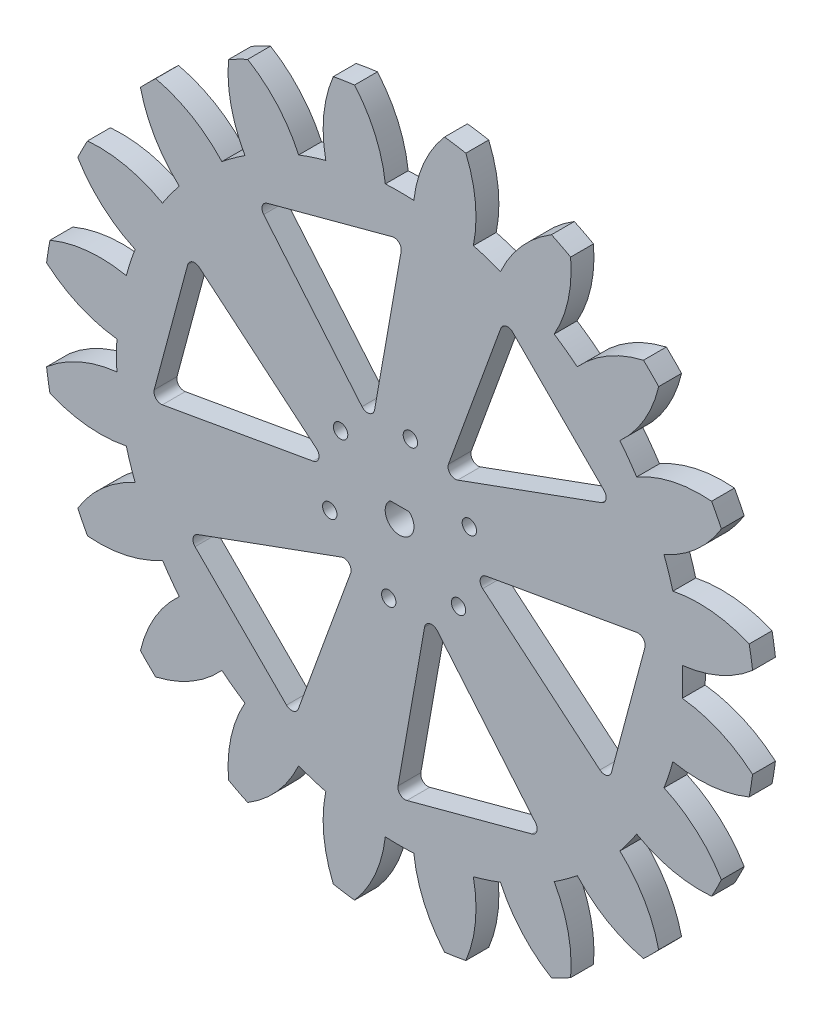
SolidWorks part; units mm, degrees
ref_plane "Front Plane" through (0, 0, 0) normal (0, 0, 1) x (1, 0, 0)
ref_plane "Top Plane" through (0, 0, 0) normal (0, 1, 0) x (1, 0, 0)
ref_plane "Right Plane" through (0, 0, 0) normal (1, 0, 0) x (0, 0, -1)
sketch "Sketch1" plane through (0, 0, 0) normal (0, 0, 1) x (1, 0, 0)
  circle A1 centre (0, 0) radius 49.5
  dimension "D1" = 99
extrude "Boss-Extrude1" add sketch "Sketch1" along normal blind 3.18 contours A1
sketch "Sketch2" plane through (0, 0, 3.18) normal (0, 0, 1) x (1, 0, 0)
  line L0 (0, 0) -> (-2.9693, 18.7471) construction
  line L1 (0, 0) -> (0, 29.1713) construction
  line L2 (-3.527, 44.8616) -> (-7.0178, 44.3087) construction
  circle A0 centre (0, 0) radius 45 construction
  circle A1 centre (0, 0) radius 42.2862 construction
  circle A2 centre (0, 0) radius 39.375 construction
  arc A3 (-6.261, 49.1024) -> (-1.9848, 39.3249) centre (-19.8734, 37.3252) cw
  circle A4 centre (0, 0) radius 49.5 construction
  arc A5 (6.261, 49.1024) -> (1.9848, 39.3249) centre (19.8734, 37.3252) ccw
  arc A6 (1.9848, 39.3249) -> (-1.9848, 39.3249) centre (0, 0) ccw
  arc A7 (6.261, 49.1024) -> (-6.261, 49.1024) centre (0, 0) ccw
  circle M7 centre (0, 0) radius 49.5
  dimension "D1" = 78.75
  dimension "D2" = 84.5723
  dimension "D3" = 90
  dimension "D5" = 18
  dimension "D4" = 9
  dimension "D7" = 3.5343
extrude "Cut-Extrude1" cut sketch "Sketch2" against normal blind 3.18 contours A6 A5 A3 M7
pattern_circular "CirPattern1" count 20 over 360 about axis through (0, 0, 0) along (0, 0, 1) of "Cut-Extrude1"
sketch "Sketch3" plane through (0, 0, 3.18) normal (0, 0, 1) x (1, 0, 0)
  line L0 (6.0689, 7.9479) -> (29.5612, 16.4984)
  line L1 (6.0689, 7.9479) -> (14.6194, 31.4402)
  line L2 (0, 0) -> (0, 16.6685) construction
  line L3 (0, 0) -> (18.2888, 0) construction
  line L4 (14.6194, 31.4402) -> (29.5612, 16.4984)
  dimension "D1" = 50
  dimension "D2" = 20
  dimension "D3" = 25
  dimension "D4" = 25
  dimension "D5" = 10
  dimension "D6" = 6.0689
extrude "Cut-Extrude2" cut sketch "Sketch3" against normal through all contours L1 L4 L0
fillet "Fillet2" radius 1 3 edges at (14.6194, 31.4402, 1.59) (29.5612, 16.4984, 1.59) (6.0689, 7.9479, 1.59)
pattern_circular "CirPattern2" count 6 over 360 about axis through (0, 0, 0) along (0, 0, 1) of "Cut-Extrude2", "Fillet2"
sketch "Sketch5" plane through (0, 0, 3.18) normal (0, 0, 1) x (1, 0, 0)
  line L0 (-1.3229, 1.5) -> (1.3229, 1.5)
  line L1 (0, 0) -> (0, 15.7807) construction
  arc A0 (1.3229, 1.5) -> (-1.3229, 1.5) centre (0, 0) cw
  dimension "D2" = 2
  dimension "D1" = 1.5
extrude "Cut-Extrude3" cut sketch "Sketch5" against normal through all
sketch "Sketch7" plane through (0, 0, 0) normal (0, 0, -1) x (-1, 0, 0)
  line L2 (4.2022, 10.5494) -> (-1.505, 10.3411) construction
  line L3 (-1.505, 10.3411) -> (-7.0349, 8.9139) construction
  circle A0 centre (-1.505, 10.3411) radius 1
  arc A1 (3.4762, 11.3417) -> (5.2271, 10.8725) centre (4.461, 11.5153) ccw construction
  arc A2 (-8.0841, 8.6813) -> (-6.8023, 9.9631) centre (-7.742, 9.621) ccw construction
  dimension "D1" = 2
  dimension "D2" = 10.45
extrude "Cut-Extrude4" cut sketch "Sketch7" against normal through all contours A0
pattern_circular "CirPattern3" count 6 over 360 about axis through (0, 0, 0) along (0, 0, 1) of "Cut-Extrude4"
equation "\"module\"= 4.5"
equation "\"teeth\" = 20"
equation "\"pressureAngle\"= 20"
equation "\"gearThickness\"= 3.18"
equation "\"addendumFactor\"= 1"
equation "\"dedendumFactor\"= 1.25"
equation "\"pitch\"= 1 / \"module\""
equation "\"pitch diameter\"= \"teeth\" / \"pitch\""
equation "\"addendum\"= \"addendumFactor\" / \"pitch\""
equation "\"dedendum\"= \"dedendumFactor\" / \"pitch\""
equation "\"D1@Sketch1\"=\"pitch diameter\"+(\"addendum\"*2)"
equation "\"D1@Boss-Extrude1\"=\"gearThickness\""
equation "\"D1@Sketch2\"=\"pitch diameter\" - 2 *\"dedendum\""
equation "\"D2@Sketch2\"=\"pitch diameter\" * cos( \"pressureAngle\")"
equation "\"D3@Sketch2\"=\"pitch diameter\""
equation "\"D4@Sketch2\"=180 / \"teeth\""
equation "\"D5@Sketch2\"=\"pitch diameter\" / 5"
equation "\"D7@Sketch2\"=PI / 2 / \"pitch\" / 2"
equation "\"D1@CirPattern1\"=\"teeth\""
